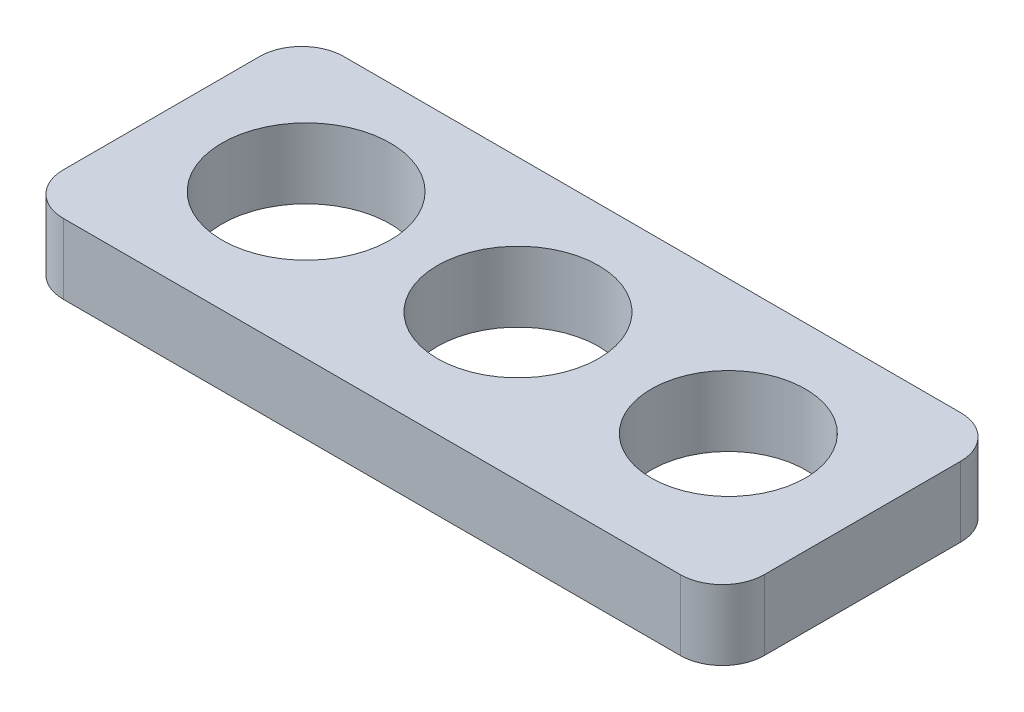
SolidWorks part; units mm, degrees
ref_plane "Front Plane" through (0, 0, 0) normal (0, 0, 1) x (1, 0, 0)
ref_plane "Top Plane" through (0, 0, 0) normal (0, 1, 0) x (1, 0, 0)
ref_plane "Right Plane" through (0, 0, 0) normal (1, 0, 0) x (0, 0, -1)
sketch "Sketch1" plane through (0, 0, 0) normal (0, 1, 0) x (1, 0, 0)
  line L1 (3, 0) -> (47, 0)
  line L2 (0, 3) -> (0, 17)
  line L3 (3, 20) -> (47, 20)
  line L4 (50, 3) -> (50, 17)
  arc A0 (3, 0) -> (0, 3) centre (3, 3) cw
  arc A1 (0, 17) -> (3, 20) centre (3, 17) cw
  arc A2 (47, 0) -> (50, 3) centre (47, 3) ccw
  arc A3 (47, 20) -> (50, 17) centre (47, 17) cw
  point P7 (0, 0)
  point P10 (0, 20)
  point P13 (50, 0)
  point P16 (50, 20)
  dimension "D3" = 3
  dimension "D1" = 50
  dimension "D2" = 20
extrude "Boss-Extrude1" add sketch "Sketch1" along normal blind 5
sketch "Sketch3" plane through (0, 5, 0) normal (0, 1, 0) x (1, 0, 0)
  line L0 (0, 17) -> (0, 3) construction
  circle A0 centre (10, 10.3169) radius 6
  circle A1 centre (24.9963, 10.4291) radius 5.75
  circle A2 centre (40, 10.4291) radius 5.5
  point P6 (0, 10)
  dimension "D1" = 10
  dimension "D3" = 40
  dimension "D4" = 12
  dimension "D5" = 11.5
  dimension "D6" = 11
  dimension "D2" = 25
extrude "Cut-Extrude3" cut sketch "Sketch3" against normal blind 5
